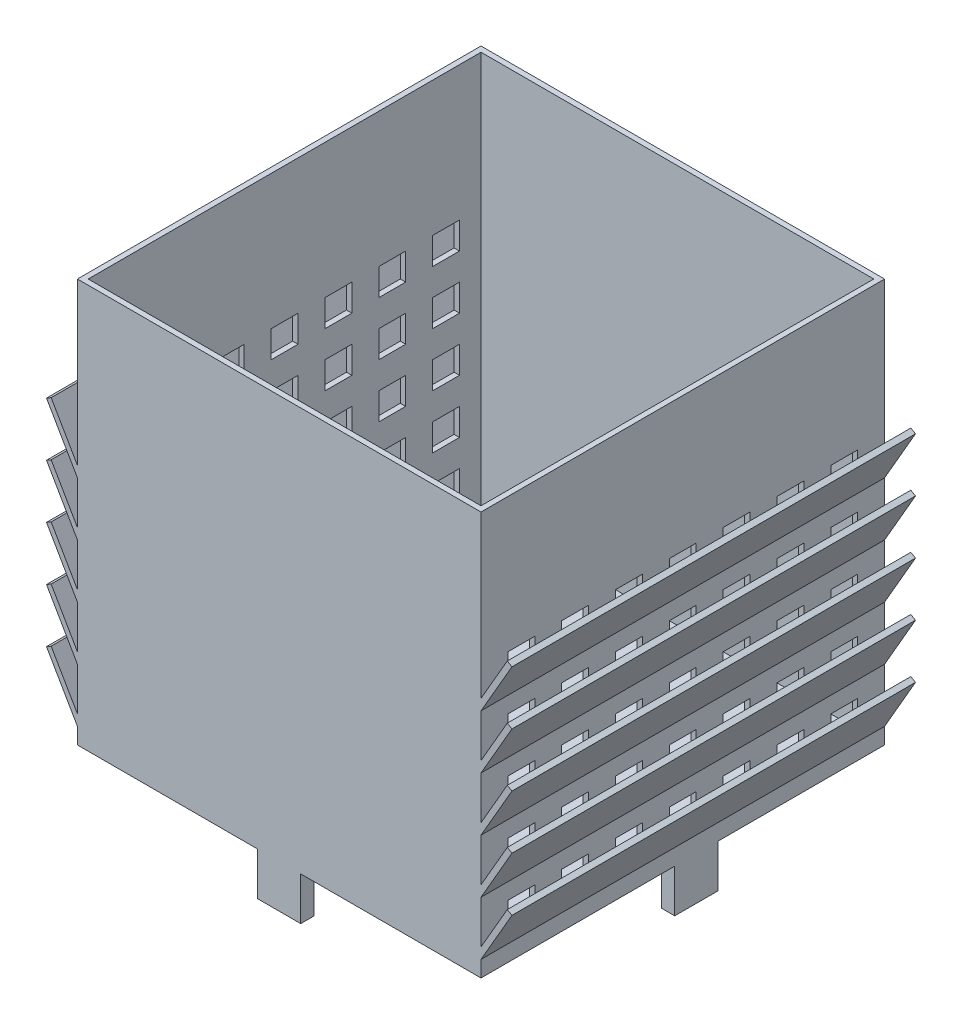
SolidWorks part; units mm, degrees
ref_plane "前视基准面" through (0, 0, 0) normal (0, 0, 1) x (1, 0, 0)
ref_plane "上视基准面" through (0, 0, 0) normal (0, 1, 0) x (1, 0, 0)
ref_plane "右视基准面" through (0, 0, 0) normal (1, 0, 0) x (0, 0, -1)
sketch "草图1" plane through (0, 0, 0) normal (0, 1, 0) x (1, 0, 0)
  line L1 (0, 0) -> (150, 0)
  line L2 (0, 0) -> (0, 150)
  line L3 (0, 150) -> (150, 150)
  line L4 (150, 0) -> (150, 150)
  dimension "D1" = 150
  dimension "D2" = 150
extrude "凸台-拉伸1" add sketch "草图1" along normal blind 150
shell "抽壳1" thickness 2
sketch "草图2" plane through (0, 0, 0) normal (-1, 0, 0) x (0, 0, 1)
  line L0 (-135, 10) -> (-135, 0) construction
  line L1 (-140, 10) -> (-130, 10)
  line L2 (-140, 10) -> (-140, 20)
  line L3 (-140, 20) -> (-130, 20)
  line L4 (-130, 10) -> (-130, 20)
  line L5 (-150, 0) -> (0, 0) construction
  line L6 (-140, 15) -> (-150, 15) construction
  line L7 (-150, 150) -> (-150, 0) construction
  dimension "D1" = 10
  dimension "D2" = 10
  dimension "D3" = 10
  dimension "D4" = 10
extrude "切除-拉伸1" cut sketch "草图2" against normal blind 474
pattern_linear "阵列(线性)1" count 5 spacing 20 along (0, 1, 0) count 7 spacing 20 along (0, 0, 1) of "切除-拉伸1"
sketch "草图3" plane through (0, 0, 0) normal (0, 0, 1) x (1, 0, 0)
  line L0 (0, 10) -> (-9.7679, 26.9186)
  line L1 (-9.7679, 26.9186) -> (-11.5, 25.9186)
  line L2 (-11.5, 25.9186) -> (0, 6)
  line L3 (0, 150) -> (0, 0) construction
  line L4 (0, 6) -> (0, 10)
  dimension "D1" = 2
  dimension "D2" = 30
  dimension "D3" = 23
extrude "凸台-拉伸2" add sketch "草图3" against normal blind 150
pattern_linear "阵列(线性)2" count 5 spacing 20 along (0, 1, 0) of "凸台-拉伸2"
sketch "草图4" plane through (0, 0, -150) normal (0, 0, -1) x (-1, 0, 0)
  line L0 (-150, 10) -> (-159.7679, 26.9186)
  line L1 (-159.7679, 26.9186) -> (-161.5, 25.9186)
  line L2 (-161.5, 25.9186) -> (-150, 6)
  line L3 (-150, 150) -> (-150, 0) construction
  line L4 (-150, 6) -> (-150, 10)
  dimension "D1" = 2
  dimension "D2" = 23
  dimension "D3" = 30
extrude "凸台-拉伸3" add sketch "草图4" against normal blind 150
pattern_linear "阵列(线性)3" count 5 spacing 20 along (0, 1, 0) of "凸台-拉伸3"
sketch "草图5" plane through (0, 0, 0) normal (0, -1, 0) x (-1, 0, 0)
  line L0 (0, 150) -> (0, 0) construction
  line L1 (0, 72) -> (-5, 72)
  line L2 (0, 72) -> (0, 88)
  line L3 (0, 88) -> (-5, 88)
  line L4 (-5, 72) -> (-5, 88)
  line L5 (-5, 80) -> (-150, 80) construction
  line L6 (-150, 0) -> (-150, 150) construction
  line L7 (-150, 88) -> (-145, 88)
  line L8 (-150, 88) -> (-150, 72)
  line L9 (-150, 72) -> (-145, 72)
  line L10 (-145, 88) -> (-145, 72)
  line L11 (0, 0) -> (-150, 0) construction
  line L12 (-67, 0) -> (-83, 0)
  line L13 (-67, 0) -> (-67, 5)
  line L14 (-67, 5) -> (-83, 5)
  line L15 (-83, 0) -> (-83, 5)
  line L16 (-75, 5) -> (-75, 150) construction
  line L17 (-150, 150) -> (0, 150) construction
  line L19 (-67, 150) -> (-83, 150)
  line L20 (-67, 150) -> (-67, 145)
  line L21 (-67, 145) -> (-83, 145)
  line L22 (-83, 150) -> (-83, 145)
  dimension "D1" = 16
  dimension "D2" = 5
  dimension "D3" = 5
  dimension "D4" = 16
  dimension "D5" = 5
  dimension "D6" = 5
extrude "凸台-拉伸4" add sketch "草图5" along normal blind 16
